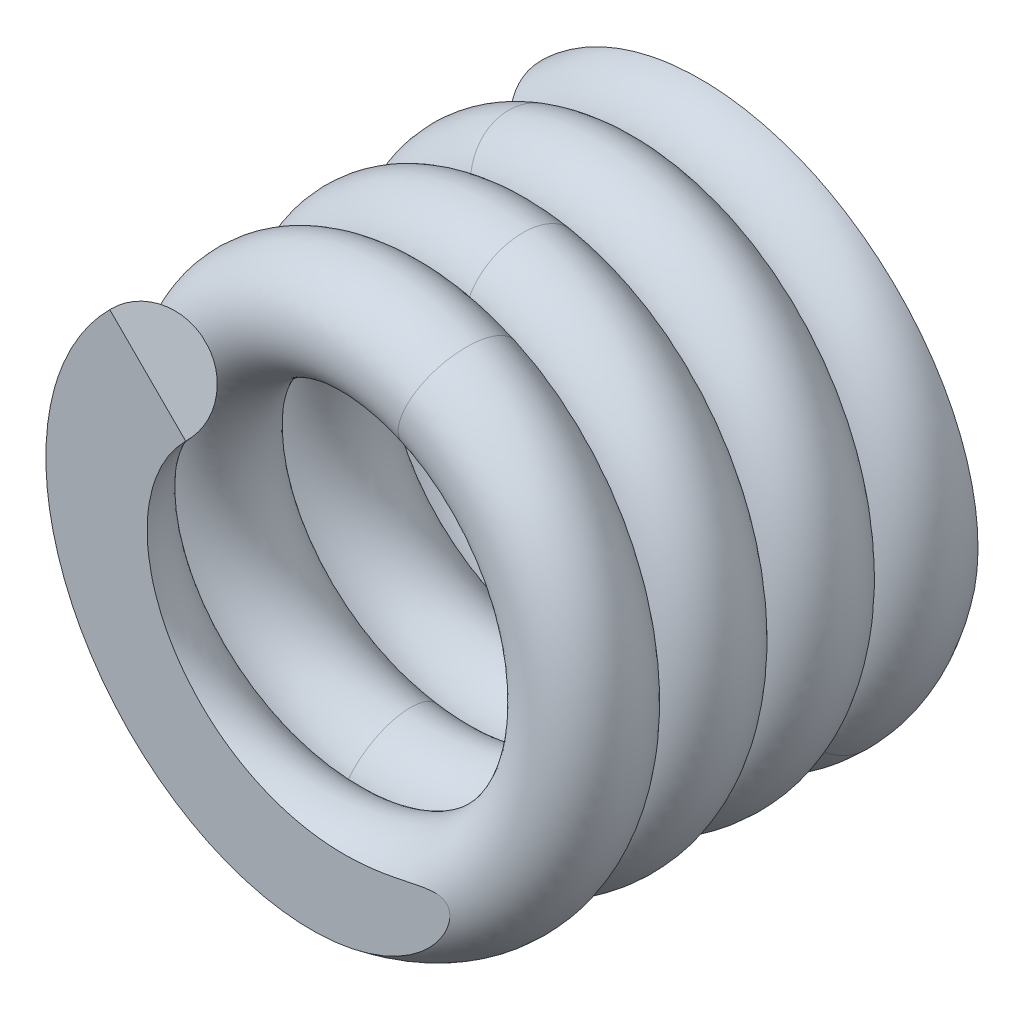
SolidWorks part; units mm, degrees
ref_plane "前视基准面" through (0, 0, 0) normal (0, 0, 1) x (1, 0, 0)
ref_plane "上视基准面" through (0, 0, 0) normal (0, 1, 0) x (1, 0, 0)
ref_plane "右视基准面" through (0, 0, 0) normal (1, 0, 0) x (0, 0, -1)
sketch "草图1" plane through (0, 0, 0) normal (0, 0, 1) x (1, 0, 0)
  circle A0 centre (0, 0) radius 2.4
  dimension "D1" = 4.8
curve "螺旋线/涡状线1" pitch 1.2 height 4.8 turns 4
sweep "扫描1" add path "螺旋线/涡状线1" circular profile diameter 1.2 parameters "D3"=1.2
sketch "草图8" plane through (0.2684, 0.2684, 0.0302) normal (0.7049, 0.7049, 0.0793) x (0.0561, 0.0561, -0.9968)
  line L1 (0, 3.5661) -> (-4.8, 3.5661)
  line L2 (0, 3.5661) -> (0, -3.4814)
  line L3 (0, -3.4814) -> (-4.8, -3.4814)
  line L4 (-4.8, 3.5661) -> (-4.8, -3.4814)
  dimension "D1" = 4.8
extrude "切除-拉伸1" cut sketch "草图8" against normal through all both and the other way through all flip side to cut
